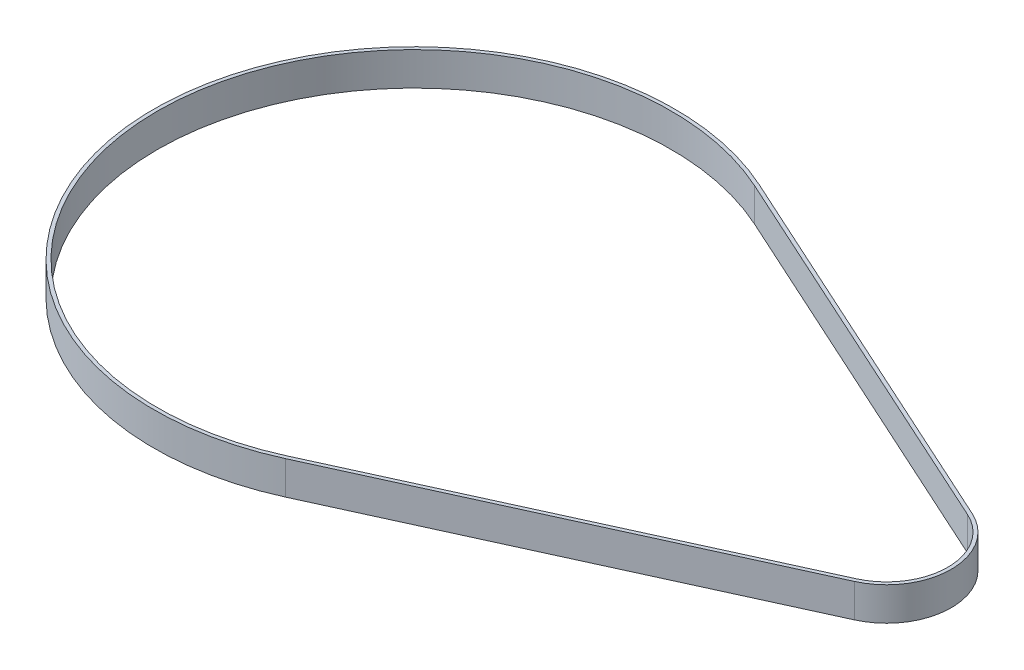
SolidWorks part; units mm, degrees
material "Rubber"
ref_plane "Front Plane" through (0, 0, 0) normal (0, 0, 1) x (1, 0, 0)
ref_plane "Top Plane" through (0, 0, 0) normal (0, 1, 0) x (1, 0, 0)
ref_plane "Right Plane" through (0, 0, 0) normal (1, 0, 0) x (0, 0, -1)
sketch "Sketch1" plane through (0, 0, 0) normal (0, 1, 0) x (1, 0, 0)
  line L0 (89.5618, 10.0095) -> (19.1801, 42.0854)
  line L1 (19.1801, -42.0854) -> (89.5618, -10.0095)
  line L2 (19.4414, -42.6587) -> (89.823, -10.5828)
  line L3 (89.823, 10.5828) -> (19.4414, 42.6587)
  arc A0 (19.1801, 42.0854) -> (19.1801, -42.0854) centre (0, 0) ccw
  arc A1 (89.5618, -10.0095) -> (89.5618, 10.0095) centre (85, 0) ccw
  arc A2 (19.4414, 42.6587) -> (19.4414, -42.6587) centre (0, 0) ccw
  arc A3 (89.823, -10.5828) -> (89.823, 10.5828) centre (85, 0) ccw
  point P9 (0, 0)
  dimension "D1" = 92.5
  dimension "D2" = 22
  dimension "D3" = 85
  dimension "D4" = 0.63
extrude "Boss-Extrude1" add sketch "Sketch1" along normal mid plane 6 contours A0 L1 A1 L0
